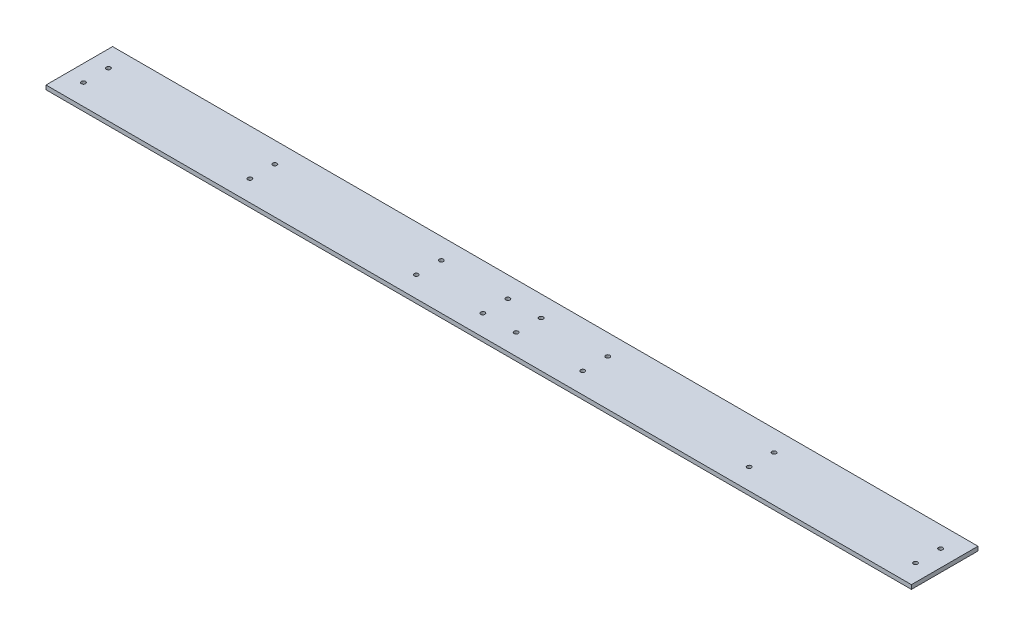
SolidWorks part; units mm, degrees
ref_plane "Front Plane" through (0, 0, 0) normal (0, 0, 1) x (1, 0, 0)
ref_plane "Top Plane" through (0, 0, 0) normal (0, 1, 0) x (1, 0, 0)
ref_plane "Right Plane" through (0, 0, 0) normal (1, 0, 0) x (0, 0, -1)
sketch "Sketch1" plane through (0, 0, 0) normal (0, 1, 0) x (1, 0, 0)
  line L0 (0, 15) -> (0, -15) construction
  line L1 (-20, 40) -> (-20, -40)
  line L2 (-20, -40) -> (1020, -40)
  line L3 (1020, -40) -> (1020, 40)
  line L4 (1020, 40) -> (-20, 40)
  line L5 (-20, 0) -> (0, 0) construction
  line L6 (0, 0) -> (1020, 0) construction
  line L7 (-78.9282, 15) -> (-78.9282, -15) construction
  line L8 (0, -15) -> (200, -15) construction
  line L9 (-78.9282, 15) -> (0, 15) construction
  line L10 (1058.1654, 5) -> (1058.1654, -25) construction
  line L11 (500, 40) -> (500, -40) construction
  line L12 (400, 15) -> (480, 15) construction
  line L13 (480, 15) -> (520, 15) construction
  line L14 (480, 15) -> (480, -15) construction
  line L15 (480, -15) -> (520, -15) construction
  line L16 (520, 15) -> (520, -15) construction
  line L17 (480, 15) -> (520, -15) construction
  line L18 (480, -15) -> (520, 15) construction
  circle A0 centre (0, 15) radius 2.5
  circle A1 centre (0, -15) radius 2.5
  circle A2 centre (200, -15) radius 2.5
  circle A3 centre (200, 15) radius 2.5
  circle A4 centre (400, -15) radius 2.5
  circle A5 centre (400, 15) radius 2.5
  circle A6 centre (600, -15) radius 2.5
  circle A7 centre (600, 15) radius 2.5
  circle A8 centre (800, -15) radius 2.5
  circle A9 centre (800, 15) radius 2.5
  circle A10 centre (1058.1654, 5) radius 2.5 construction
  circle A11 centre (1058.1654, -25) radius 2.5 construction
  circle A12 centre (-78.9282, -15) radius 2.5 construction
  circle A13 centre (-78.9282, 15) radius 2.5 construction
  circle A14 centre (1000, -15) radius 2.5
  circle A15 centre (1000, 15) radius 2.5
  circle A16 centre (480, 15) radius 2.5
  circle A17 centre (520, 15) radius 2.5
  circle A18 centre (520, -15) radius 2.5
  circle A19 centre (480, -15) radius 2.5
  point P39 (500, 0)
  dimension "D2" = 5
  dimension "D9" = 80
  dimension "D1" = 30
  dimension "D3" = 20
  dimension "D4" = 20
  dimension "D5" = 6
  dimension "D6" = 200
  dimension "D7" = 40
extrude "Boss-Extrude1" add sketch "Sketch1" along normal blind 5
equation "\"skin_sheetmetal_thickness\"= 0.80"
equation "\"base_width_skin_spacer\" = \"base_width_skin_target_width\" - 4 * \"skin_sheetmetal_thickness\" - 2 * \"base_width_skin_target_bend_radius\""
equation "\"base_width_skin_inner\" = \"base_width_skin_spacer\" + 2 * \"skin_sheetmetal_thickness\""
equation "\"base_width_skin_outer\" = \"base_width_skin_inner\" + 2 * \"skin_sheetmetal_thickness\""
equation "\"bend_cut_width\"= 3"
equation "\"bend_cut_length\"= 3"
equation "\"bend_offset_inner\"= 12.5"
equation "\"bend_offset_outer\" = \"bend_offset_inner\" + \"skin_sheetmetal_thickness\""
equation "\"border_offset_ends\"= 20"
equation "\"border_offset_sides\"= 10"
equation "\"border_offset_flange_horiz\"= 10"
equation "\"rivet_size\"= 4.3"
equation "\"rivet_offset_ends\"= \"rivet_spacing_horiz\"/2 - \"border_offset_ends\""
equation "\"rivet_spacing_horiz\"= 100"
equation "\"rivet_spacing_vert\"= 30"
equation "\"rivet_spacing_offset_right\"= 40"
equation "\"base_length\"= 200"
